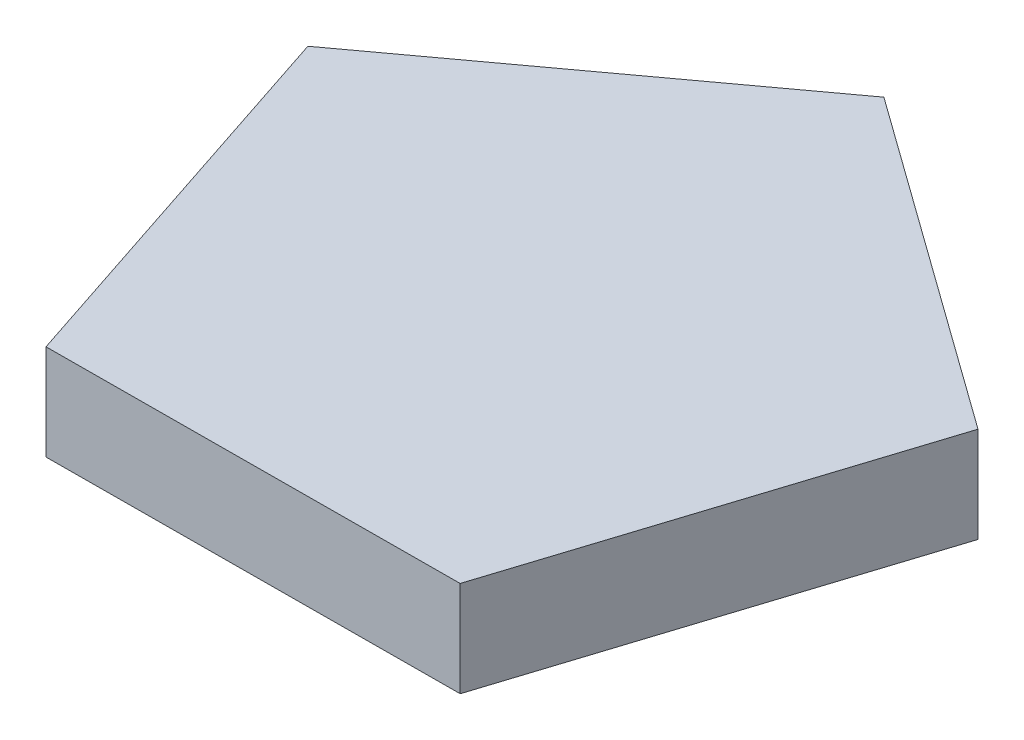
SolidWorks part; units mm, degrees
ref_plane "前视基准面" through (0, 0, 0) normal (0, 0, 1) x (1, 0, 0)
ref_plane "上视基准面" through (0, 0, 0) normal (0, 1, 0) x (1, 0, 0)
ref_plane "右视基准面" through (0, 0, 0) normal (1, 0, 0) x (0, 0, -1)
other "Configuration Table"
sketch "草图1" plane through (0, 0, 0) normal (0, 1, 0) x (1, 0, 0)
  line L1 (3.174, -14.0325) -> (16.2893, 27.053)
  line L2 (16.2893, 27.053) -> (-18.7325, 52.2225)
  line L3 (-18.7325, 52.2225) -> (-53.4924, 26.6926)
  line L4 (-53.4924, 26.6926) -> (-39.9535, -14.2553)
  line L5 (-39.9535, -14.2553) -> (3.174, -14.0325)
  circle A0 centre (-18.543, 15.536) radius 29.6803 construction
extrude "凸台-拉伸1" add sketch "草图1" along normal blind 10
